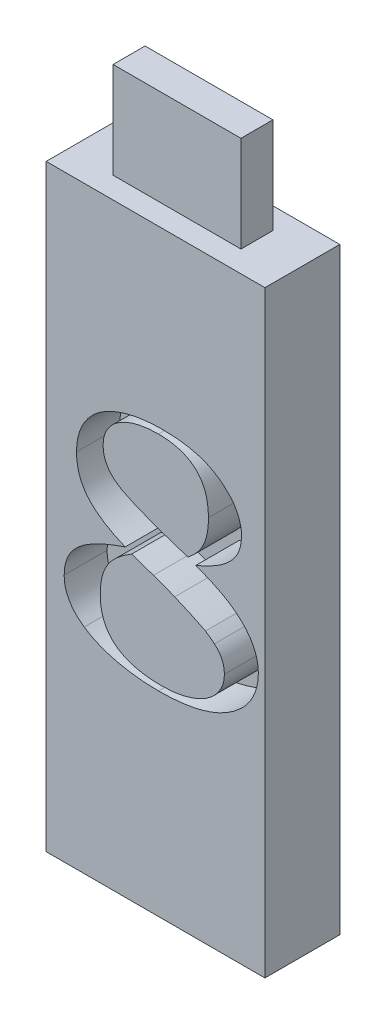
SolidWorks part; units mm, degrees
ref_plane "Front Plane" through (0, 0, 0) normal (0, 0, 1) x (1, 0, 0)
ref_plane "Top Plane" through (0, 0, 0) normal (0, 1, 0) x (1, 0, 0)
ref_plane "Right Plane" through (0, 0, 0) normal (1, 0, 0) x (0, 0, -1)
sketch "Sketch1" plane through (0, 0, 0) normal (0, 0, 1) x (1, 0, 0)
  line L1 (-8.69, -23.749) -> (8.69, -23.749)
  line L2 (-8.69, -23.749) -> (-8.69, 23.749)
  line L3 (-8.69, 23.749) -> (8.69, 23.749)
  line L4 (8.69, -23.749) -> (8.69, 23.749)
  line L5 (-8.69, -23.749) -> (8.69, 23.749) construction
  line L6 (-8.69, 23.749) -> (8.69, -23.749) construction
  point P0 (0, 0)
  dimension "D1" = 17.38
  dimension "D2" = 47.498
extrude "Boss-Extrude1" add sketch "Sketch1" along normal blind 5.95
sketch "Sketch2" plane through (0, 0, 5.95) normal (0, 0, 1) x (1, 0, 0)
  line L0 (0, 23.749) -> (0, -23.749) construction
  line L1 (8.69, 23.749) -> (-8.69, 23.749) construction
  line L2 (-8.69, -23.749) -> (8.69, -23.749) construction
  line L3 (0, -23.749) -> (0, 0) construction
  line L4 (0, 0) -> (-8.69, 0) construction
  line L5 (-8.69, 23.749) -> (-8.69, -23.749) construction
  line L6 (-8.69, 0) -> (8.69, 0) construction
  line L7 (8.69, -23.749) -> (8.69, 23.749) construction
  line L8 (-8.69, -23.749) -> (8.69, -23.749) construction
  line L9 (-8.69, -21.209) -> (8.69, -21.209) construction
  line L10 (-8.69, -18.669) -> (8.69, -18.669) construction
  line L11 (-8.69, -16.129) -> (8.69, -16.129) construction
  line L12 (-8.69, -13.589) -> (8.69, -13.589) construction
  line L13 (-8.69, -11.049) -> (8.69, -11.049) construction
  line L14 (-8.69, -8.509) -> (8.69, -8.509) construction
  line L15 (-8.69, -5.969) -> (8.69, -5.969) construction
  line L16 (-8.69, -3.429) -> (8.69, -3.429) construction
  line L17 (-8.69, -0.889) -> (8.69, -0.889) construction
  line L18 (-8.69, 1.651) -> (8.69, 1.651) construction
  line L19 (-8.69, 4.191) -> (8.69, 4.191) construction
  line L20 (-8.69, 6.731) -> (8.69, 6.731) construction
  line L21 (-8.69, 9.271) -> (8.69, 9.271) construction
  line L22 (-8.69, 11.811) -> (8.69, 11.811) construction
  line L23 (-8.69, 14.351) -> (8.69, 14.351) construction
  line L24 (-8.69, 16.891) -> (8.69, 16.891) construction
  line L25 (-8.69, 19.431) -> (8.69, 19.431) construction
  line L26 (-8.69, 21.971) -> (8.69, 21.971) construction
  line L27 (-8.69, 23.749) -> (-8.69, -23.749) construction
  line L28 (-6.15, 23.749) -> (-6.15, -23.749) construction
  line L29 (-3.61, 23.749) -> (-3.61, -23.749) construction
  line L30 (-1.07, 23.749) -> (-1.07, -23.749) construction
  line L31 (1.47, 23.749) -> (1.47, -23.749) construction
  line L32 (4.01, 23.749) -> (4.01, -23.749) construction
  line L33 (6.55, 23.749) -> (6.55, -23.749) construction
  text T0 "8" font "Engravers MT" height in points 72
  dimension "D1" = 19
  dimension "D2" = 2.54
  dimension "D4" = 2.54
  dimension "D3" = 7
extrude "Cut-Extrude1" cut sketch "Sketch2" against normal blind 3.41
sketch "Sketch3" plane through (0, 23.749, 0) normal (0, 1, 0) x (1, 0, 0)
  line L0 (0, 0) -> (0, -5.95) construction
  line L1 (8.69, -5.95) -> (-8.69, -5.95) construction
  line L2 (0, -5.95) -> (0, -2.975) construction
  line L3 (0, -2.975) -> (-8.69, -2.975) construction
  line L4 (-8.69, -5.95) -> (-8.69, 0) construction
  line L5 (-8.69, -2.975) -> (8.69, -2.975) construction
  line L6 (8.69, -5.95) -> (8.69, 0) construction
  line L8 (-5.08, -4.245) -> (5.08, -4.245)
  line L9 (-5.08, -4.245) -> (-5.08, -1.705)
  line L10 (-5.08, -1.705) -> (5.08, -1.705)
  line L11 (5.08, -4.245) -> (5.08, -1.705)
  line L12 (-5.08, -4.245) -> (5.08, -1.705) construction
  line L13 (-5.08, -1.705) -> (5.08, -4.245) construction
  dimension "D1" = 2.54
  dimension "D2" = 10.16
extrude "Boss-Extrude2" add sketch "Sketch3" along normal blind 7.62
